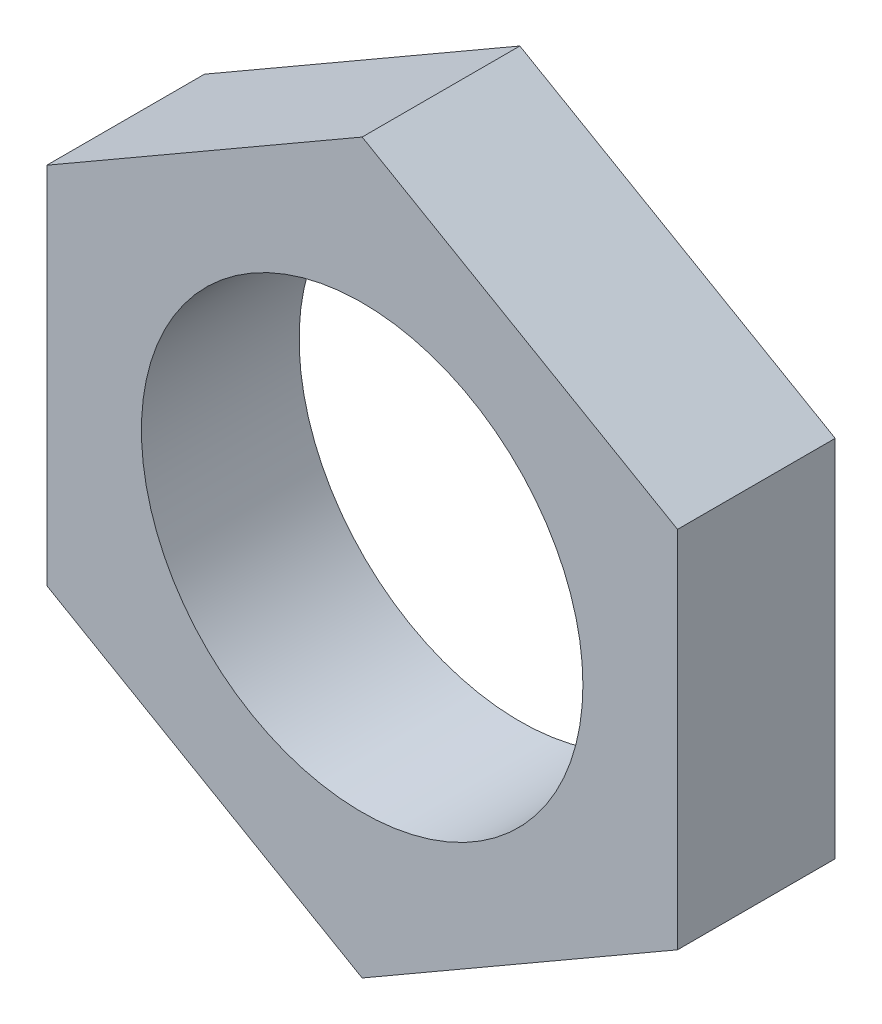
SolidWorks part; units mm, degrees
ref_plane "Спереди" through (0, 0, 0) normal (0, 0, 1) x (1, 0, 0)
ref_plane "Сверху" through (0, 0, 0) normal (0, 1, 0) x (1, 0, 0)
ref_plane "Справа" through (0, 0, 0) normal (1, 0, 0) x (0, 0, -1)
sketch "Эскиз1" plane through (0, 0, 0) normal (0, 0, 1) x (1, 0, 0)
  line L1 (0, 4.6188) -> (-4, 2.3094)
  line L2 (-4, 2.3094) -> (-4, -2.3094)
  line L3 (-4, -2.3094) -> (0, -4.6188)
  line L4 (0, -4.6188) -> (4, -2.3094)
  line L5 (4, -2.3094) -> (4, 2.3094)
  line L6 (4, 2.3094) -> (0, 4.6188)
  circle A0 centre (0, 0) radius 4 construction
  circle A1 centre (0, 0) radius 2.8
  dimension "D1" = 5.6
  dimension "D2" = 8
extrude "Вытянуть1" add sketch "Эскиз1" along normal blind 2
